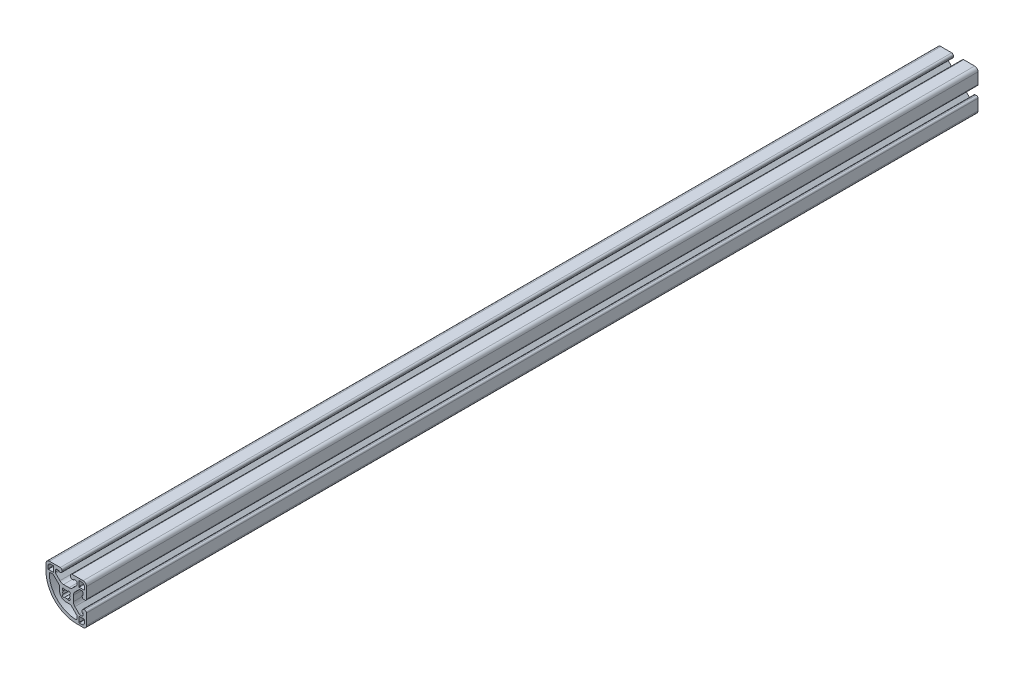
SolidWorks part; units mm, degrees
ref_plane "Front Plane" through (0, 0, 0) normal (0, 0, 1) x (1, 0, 0)
ref_plane "Top Plane" through (0, 0, 0) normal (0, 1, 0) x (1, 0, 0)
ref_plane "Right Plane" through (0, 0, 0) normal (1, 0, 0) x (0, 0, -1)
ref_plane "Plane1" through (0, 0, 838.2) normal (0, 0, 1) x (1, 0, 0)
sketch "Sketch1" plane through (0, 0, 838.2) normal (0, 0, 1) x (1, 0, 0)
  line L0 (-14.4526, 17.2466) -> (-12.2428, 17.2466)
  line L1 (-11.8618, 16.8656) -> (-11.8618, 12.2428)
  line L2 (-12.2428, 11.8618) -> (-16.8656, 11.8618)
  line L3 (-17.2466, 12.2428) -> (-17.2466, 14.4526)
  line L4 (-14.7267, 10.287) -> (-12.804, 10.287)
  line L5 (-12.1754, 10.0266) -> (-6.6966, 4.5478)
  line L6 (-6.3246, 3.6498) -> (-6.3246, 0)
  line L7 (0, -6.3246) -> (3.6498, -6.3246)
  line L8 (4.5478, -6.6966) -> (10.0266, -12.1754)
  line L9 (10.287, -12.804) -> (10.287, -14.7267)
  line L10 (-3.4372, -1.8208) -> (-3.0179, -1.4014)
  line L11 (-3.0179, 1.4014) -> (-3.4372, 1.8208)
  line L12 (-1.8208, 3.4372) -> (-1.4014, 3.0179)
  line L13 (1.4014, 3.0179) -> (1.8208, 3.4372)
  line L14 (3.4372, 1.8208) -> (3.0179, 1.4014)
  line L15 (3.0179, -1.4014) -> (3.4372, -1.8208)
  line L16 (1.8208, -3.4372) -> (1.4014, -3.0179)
  line L17 (-1.4014, -3.0179) -> (-1.8208, -3.4372)
  line L18 (12.2428, 17.2466) -> (14.4526, 17.2466)
  line L19 (17.2466, 14.4526) -> (17.2466, 12.2428)
  line L20 (16.8656, 11.8618) -> (12.2428, 11.8618)
  line L21 (11.8618, 12.2428) -> (11.8618, 16.8656)
  line L22 (11.8618, -16.8656) -> (11.8618, -12.2428)
  line L23 (12.2428, -11.8618) -> (16.8656, -11.8618)
  line L24 (17.2466, -12.2428) -> (17.2466, -14.4526)
  line L25 (14.4526, -17.2466) -> (12.2428, -17.2466)
  line L26 (-19.05, 15.875) -> (-19.05, 9.525)
  line L27 (9.525, -19.05) -> (15.875, -19.05)
  line L28 (19.05, -15.875) -> (19.05, -5.6388)
  line L29 (17.4752, -4.064) -> (16.5608, -4.064)
  line L30 (14.986, -5.6388) -> (14.986, -6.477)
  line L31 (15.367, -6.858) -> (15.4432, -6.858)
  line L32 (15.8242, -7.239) -> (15.8242, -9.017)
  line L33 (14.5542, -10.287) -> (12.9683, -10.287)
  line L34 (12.0703, -9.915) -> (8.1222, -5.9669)
  line L35 (6.731, -2.6083) -> (6.731, 2.6083)
  line L36 (8.1222, 5.9669) -> (12.0703, 9.915)
  line L37 (12.9683, 10.287) -> (14.5542, 10.287)
  line L38 (15.8242, 9.017) -> (15.8242, 7.239)
  line L39 (15.4432, 6.858) -> (15.367, 6.858)
  line L40 (14.986, 6.477) -> (14.986, 5.6388)
  line L41 (16.5608, 4.064) -> (17.4752, 4.064)
  line L42 (19.05, 5.6388) -> (19.05, 15.875)
  line L43 (15.875, 19.05) -> (5.6388, 19.05)
  line L44 (4.064, 17.4752) -> (4.064, 16.5608)
  line L45 (5.6388, 14.986) -> (6.477, 14.986)
  line L46 (6.858, 15.367) -> (6.858, 15.4432)
  line L47 (7.239, 15.8242) -> (9.017, 15.8242)
  line L48 (10.287, 14.5542) -> (10.287, 12.9683)
  line L49 (9.915, 12.0703) -> (5.9669, 8.1222)
  line L50 (2.6083, 6.731) -> (-2.6083, 6.731)
  line L51 (-5.9669, 8.1222) -> (-9.915, 12.0703)
  line L52 (-10.287, 12.9683) -> (-10.287, 14.5542)
  line L53 (-9.017, 15.8242) -> (-7.239, 15.8242)
  line L54 (-6.858, 15.4432) -> (-6.858, 15.367)
  line L55 (-6.477, 14.986) -> (-5.6388, 14.986)
  line L56 (-4.064, 16.5608) -> (-4.064, 17.4752)
  line L57 (-5.6388, 19.05) -> (-15.875, 19.05)
  arc A0 (-17.2466, 14.4526) -> (-14.4526, 17.2466) centre (-14.4526, 14.4526) cw
  arc A1 (-12.2428, 17.2466) -> (-11.8618, 16.8656) centre (-12.2428, 16.8656) cw
  arc A2 (-11.8618, 12.2428) -> (-12.2428, 11.8618) centre (-12.2428, 12.2428) cw
  arc A3 (-16.8656, 11.8618) -> (-17.2466, 12.2428) centre (-16.8656, 12.2428) cw
  arc A4 (-12.804, 10.287) -> (-12.1754, 10.0266) centre (-12.804, 9.398) cw
  arc A5 (-6.6966, 4.5478) -> (-6.3246, 3.6498) centre (-7.5946, 3.6498) cw
  arc A6 (-6.3246, 0) -> (0, -6.3246) centre (0, 0) ccw
  arc A7 (3.6498, -6.3246) -> (4.5478, -6.6966) centre (3.6498, -7.5946) cw
  arc A8 (10.0266, -12.1754) -> (10.287, -12.804) centre (9.398, -12.804) cw
  arc A9 (10.287, -14.7267) -> (8.9904, -15.9964) centre (9.017, -14.7267) cw
  arc A10 (8.9904, -15.9964) -> (-15.9964, 8.9904) centre (9.525, 9.525) cw
  arc A11 (-15.9964, 8.9904) -> (-14.7267, 10.287) centre (-14.7267, 9.017) cw
  arc A12 (-3.0179, -1.4014) -> (-3.0179, 1.4014) centre (0, 0) cw
  arc A13 (-3.4372, 1.8208) -> (-1.8208, 3.4372) centre (-2.629, 2.629) cw
  arc A14 (-1.4014, 3.0179) -> (1.4014, 3.0179) centre (0, 0) cw
  arc A15 (1.8208, 3.4372) -> (3.4372, 1.8208) centre (2.629, 2.629) cw
  arc A16 (3.0179, 1.4014) -> (3.0179, -1.4014) centre (0, 0) cw
  arc A17 (3.4372, -1.8208) -> (1.8208, -3.4372) centre (2.629, -2.629) cw
  arc A18 (1.4014, -3.0179) -> (-1.4014, -3.0179) centre (0, 0) cw
  arc A19 (-1.8208, -3.4372) -> (-3.4372, -1.8208) centre (-2.629, -2.629) cw
  arc A20 (11.8618, 16.8656) -> (12.2428, 17.2466) centre (12.2428, 16.8656) cw
  arc A21 (14.4526, 17.2466) -> (17.2466, 14.4526) centre (14.4526, 14.4526) cw
  arc A22 (17.2466, 12.2428) -> (16.8656, 11.8618) centre (16.8656, 12.2428) cw
  arc A23 (12.2428, 11.8618) -> (11.8618, 12.2428) centre (12.2428, 12.2428) cw
  arc A24 (11.8618, -12.2428) -> (12.2428, -11.8618) centre (12.2428, -12.2428) cw
  arc A25 (16.8656, -11.8618) -> (17.2466, -12.2428) centre (16.8656, -12.2428) cw
  arc A26 (17.2466, -14.4526) -> (14.4526, -17.2466) centre (14.4526, -14.4526) cw
  arc A27 (12.2428, -17.2466) -> (11.8618, -16.8656) centre (12.2428, -16.8656) cw
  arc A28 (-19.05, 9.525) -> (9.525, -19.05) centre (9.525, 9.525) ccw
  arc A29 (15.875, -19.05) -> (19.05, -15.875) centre (15.875, -15.875) ccw
  arc A30 (19.05, -5.6388) -> (17.4752, -4.064) centre (17.4752, -5.6388) ccw
  arc A31 (16.5608, -4.064) -> (14.986, -5.6388) centre (16.5608, -5.6388) ccw
  arc A32 (14.986, -6.477) -> (15.367, -6.858) centre (15.367, -6.477) ccw
  arc A33 (15.4432, -6.858) -> (15.8242, -7.239) centre (15.4432, -7.239) cw
  arc A34 (15.8242, -9.017) -> (14.5542, -10.287) centre (14.5542, -9.017) cw
  arc A35 (12.9683, -10.287) -> (12.0703, -9.915) centre (12.9683, -9.017) cw
  arc A36 (8.1222, -5.9669) -> (6.731, -2.6083) centre (11.4808, -2.6083) cw
  arc A37 (6.731, 2.6083) -> (8.1222, 5.9669) centre (11.4808, 2.6083) cw
  arc A38 (12.0703, 9.915) -> (12.9683, 10.287) centre (12.9683, 9.017) cw
  arc A39 (14.5542, 10.287) -> (15.8242, 9.017) centre (14.5542, 9.017) cw
  arc A40 (15.8242, 7.239) -> (15.4432, 6.858) centre (15.4432, 7.239) cw
  arc A41 (15.367, 6.858) -> (14.986, 6.477) centre (15.367, 6.477) ccw
  arc A42 (14.986, 5.6388) -> (16.5608, 4.064) centre (16.5608, 5.6388) ccw
  arc A43 (17.4752, 4.064) -> (19.05, 5.6388) centre (17.4752, 5.6388) ccw
  arc A44 (19.05, 15.875) -> (15.875, 19.05) centre (15.875, 15.875) ccw
  arc A45 (5.6388, 19.05) -> (4.064, 17.4752) centre (5.6388, 17.4752) ccw
  arc A46 (4.064, 16.5608) -> (5.6388, 14.986) centre (5.6388, 16.5608) ccw
  arc A47 (6.477, 14.986) -> (6.858, 15.367) centre (6.477, 15.367) ccw
  arc A48 (6.858, 15.4432) -> (7.239, 15.8242) centre (7.239, 15.4432) cw
  arc A49 (9.017, 15.8242) -> (10.287, 14.5542) centre (9.017, 14.5542) cw
  arc A50 (10.287, 12.9683) -> (9.915, 12.0703) centre (9.017, 12.9683) cw
  arc A51 (5.9669, 8.1222) -> (2.6083, 6.731) centre (2.6083, 11.4808) cw
  arc A52 (-2.6083, 6.731) -> (-5.9669, 8.1222) centre (-2.6083, 11.4808) cw
  arc A53 (-9.915, 12.0703) -> (-10.287, 12.9683) centre (-9.017, 12.9683) cw
  arc A54 (-10.287, 14.5542) -> (-9.017, 15.8242) centre (-9.017, 14.5542) cw
  arc A55 (-7.239, 15.8242) -> (-6.858, 15.4432) centre (-7.239, 15.4432) cw
  arc A56 (-6.858, 15.367) -> (-6.477, 14.986) centre (-6.477, 15.367) ccw
  arc A57 (-5.6388, 14.986) -> (-4.064, 16.5608) centre (-5.6388, 16.5608) ccw
  arc A58 (-4.064, 17.4752) -> (-5.6388, 19.05) centre (-5.6388, 17.4752) ccw
  arc A59 (-15.875, 19.05) -> (-19.05, 15.875) centre (-15.875, 15.875) ccw
extrude "Boss-Extrude1" add sketch "Sketch1" against normal blind 838.2
